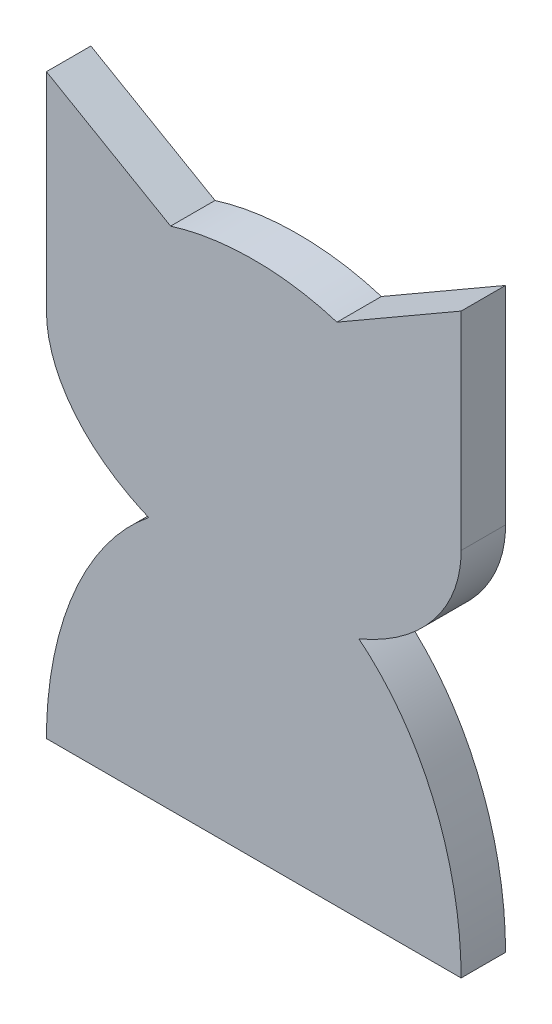
SolidWorks part; units mm, degrees
ref_plane "Alzado" through (0, 0, 0) normal (0, 0, 1) x (1, 0, 0)
ref_plane "Planta" through (0, 0, 0) normal (0, 1, 0) x (1, 0, 0)
ref_plane "Vista lateral" through (0, 0, 0) normal (1, 0, 0) x (0, 0, -1)
sketch "Croquis1" plane through (0, 0, 0) normal (0, 0, 1) x (1, 0, 0)
  line L2 (39, 0) -> (50, 0) construction
  line L5 (0, 0) -> (11, 0) construction
  line L6 (0, 0) -> (0, 40) construction
  line L7 (0, 40) -> (50, 40) construction
  line L8 (50, 0) -> (50, 40) construction
  line L13 (11, 25) -> (11, 39)
  line L14 (11, 39) -> (19.3833, 34.1599)
  line L15 (39, 39) -> (30.6167, 34.1599)
  line L16 (39, 25) -> (39, 39)
  line L17 (11, 0) -> (39, 0)
  ellipse E0 centre (25, 25) end of major axis (11, 25) minor radius 10 (11, 25) -> (17.9049, 16.3793) ccw
  ellipse E1 centre (25, 25) end of major axis (11, 25) minor radius 10 (30.6167, 34.1599) -> (19.3833, 34.1599) ccw
  ellipse E2 centre (25, 0) end of major axis (25, 19) minor radius 14 (17.9049, 16.3793) -> (11, 0) ccw
  ellipse E3 centre (25, 25) end of major axis (11, 25) minor radius 10 (32.0951, 16.3793) -> (39, 25) ccw
  ellipse E4 centre (25, 0) end of major axis (25, 19) minor radius 14 (39, 0) -> (32.0951, 16.3793) ccw
  dimension "D1" = 40
  dimension "D2" = 50
  dimension "D3" = 14
  dimension "D4" = 10
  dimension "D5" = 15
  dimension "D6" = 60
  dimension "D7" = 14
  dimension "D8" = 4
  dimension "D9" = 14
extrude "Saliente-Extruir2" add sketch "Croquis1" along normal blind 3 contours E0 E2 L17 E4 E3 L16 L15 E1 L14 L13
